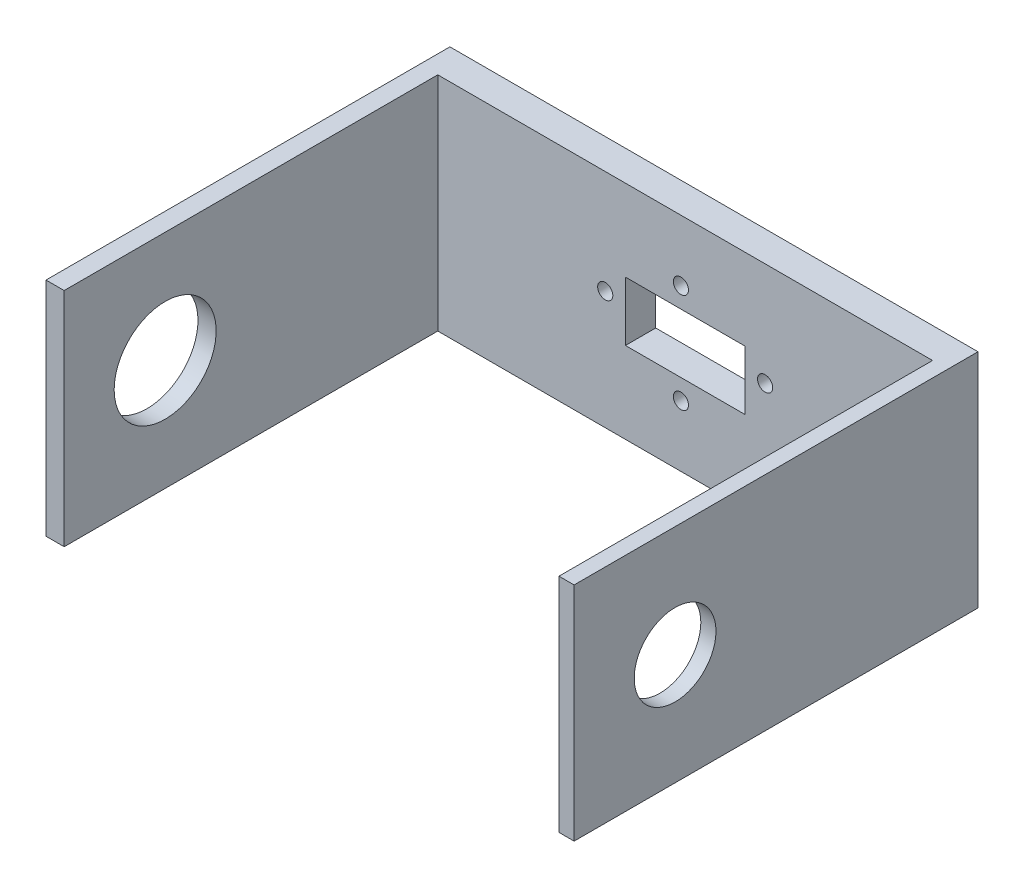
SolidWorks part; units mm, degrees
ref_plane "Plano frontal" through (0, 0, 0) normal (0, 0, 1) x (1, 0, 0)
ref_plane "Plano superior" through (0, 0, 0) normal (0, 1, 0) x (1, 0, 0)
ref_plane "Plano direito" through (0, 0, 0) normal (1, 0, 0) x (0, 0, -1)
sketch "Esboço1" plane through (0, 0, 0) normal (0, 0, 1) x (1, 0, 0)
  line L0 (0, 2.9328) -> (0, -2.9328) construction
  line L1 (-24.5, -10.9882) -> (24.5, -10.9882)
  line L2 (-24.5, -10.9882) -> (-24.5, 10.9882)
  line L3 (-24.5, 10.9882) -> (24.5, 10.9882)
  line L4 (24.5, -10.9882) -> (24.5, 10.9882)
  line L5 (-24.5, -10.9882) -> (24.5, 10.9882) construction
  line L6 (-24.5, 10.9882) -> (24.5, -10.9882) construction
  line L7 (-5.916, -2.9328) -> (5.916, -2.9328)
  line L8 (-5.916, -2.9328) -> (-5.916, 2.9328)
  line L9 (-5.916, 2.9328) -> (5.916, 2.9328)
  line L10 (5.916, -2.9328) -> (5.916, 2.9328)
  line L11 (-5.916, -2.9328) -> (5.916, 2.9328) construction
  line L12 (-5.916, 2.9328) -> (5.916, -2.9328) construction
  line L13 (5.916, 0) -> (-5.916, 0) construction
  circle A0 centre (-0.4219, 4.9328) radius 0.7509
  circle A1 centre (7.916, 0.7299) radius 0.7509
  circle A2 centre (-0.4219, -4.9328) radius 0.7509
  circle A3 centre (-7.916, 0.7299) radius 0.7509
  point P0 (0, 0)
  point P6 (0, 0)
  dimension "D1" = 2
  dimension "D2" = 2
extrude "Ressalto-extrusão1" add sketch "Esboço1" along normal blind 3
ref_plane "Plano1" through (-24.5, 0, 0) normal (-1, 0, 0) x (0, 0, 1)
sketch "Esboço2" plane through (-24.5, 0, 0) normal (-1, 0, 0) x (0, 0, 1)
  line L0 (0, 10.9882) -> (0, -10.9882)
  line L1 (0, 10.9882) -> (40, 10.9882)
  line L2 (0, -10.9882) -> (40, -10.9882)
  line L3 (40, 10.9882) -> (40, -10.9882)
  line L4 (0, 0) -> (40, 0) construction
  line L5 (20, 10.9882) -> (20, -10.9882) construction
  circle A0 centre (30, 0) radius 5.05
  dimension "D1" = 30
extrude "Ressalto-extrusão2" add sketch "Esboço2" along normal blind 1.8
ref_plane "Plano2" through (24.5, 0, 0) normal (1, 0, 0) x (0, 0, -1)
sketch "Esboço3" plane through (24.5, 0, 0) normal (1, 0, 0) x (0, 0, -1)
  line L0 (0, 10.9882) -> (0, -10.9882)
  line L1 (0, 10.9882) -> (-40, 10.9882)
  line L2 (0, -10.9882) -> (-40, -10.9882)
  line L3 (-40, 10.9882) -> (-40, -10.9882)
  line L4 (-3, 10.9882) -> (0, 10.9882) construction
  circle A0 centre (-30, 0) radius 4.05
extrude "Ressalto-extrusão3" add sketch "Esboço3" along normal blind 1.5
